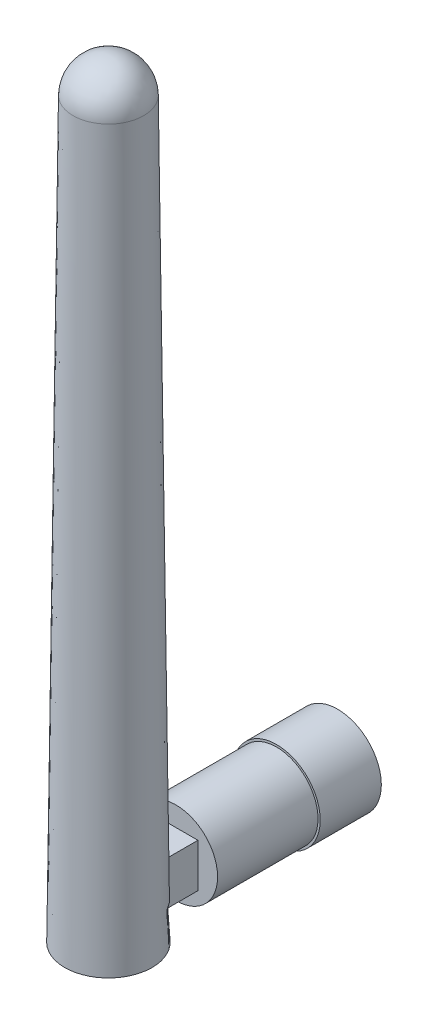
SolidWorks part; units mm, degrees
ref_plane "Front Plane" through (0, 0, 0) normal (0, 0, 1) x (1, 0, 0)
ref_plane "Top Plane" through (0, 0, 0) normal (0, 1, 0) x (1, 0, 0)
ref_plane "Right Plane" through (0, 0, 0) normal (1, 0, 0) x (0, 0, -1)
sketch "Sketch1" plane through (0, 0, 0) normal (0, 0, 1) x (1, 0, 0)
  circle A0 centre (0, 0) radius 5
  dimension "D1" = 10
extrude "Boss-Extrude1" add sketch "Sketch1" along normal blind 7
sketch "Sketch2" plane through (0, 0, 7) normal (0, 0, 1) x (1, 0, 0)
  circle A0 centre (0, 0) radius 4.75
  dimension "D1" = 9.5
extrude "Boss-Extrude2" add sketch "Sketch2" along normal blind 11.5
sketch "Sketch3" plane through (0, 0, 0) normal (0, 1, 0) x (1, 0, 0)
  line L0 (5, 0) -> (-5, 0) construction
  circle A0 centre (0, -26.25) radius 4.75
  dimension "D1" = 9.5
  dimension "D2" = 31
ref_plane "Plane1" through (0, 0, 26.25) normal (0, 0, 1) x (1, 0, 0)
sketch "Sketch4" plane through (0, 0, 26.25) normal (0, 0, 1) x (1, 0, 0)
  line L0 (0, -5) -> (-5, -5)
  line L1 (-5, -5) -> (-4.0455, 79.0003)
  line L2 (0, -1000) -> (0, 49000) construction
  line L3 (4.75, 0) -> (-4.75, 0) construction
  line L6 (0, 83) -> (0, -5)
  circle A0 centre (0, 0) radius 5 construction
  arc A2 (0, 83) -> (-4.0455, 79.0003) centre (0, 78.9543) ccw
  point P10 (0, 0)
  point P12 (0, 83)
  point P13 (0, -5)
  dimension "D1" = 4.0457
  dimension "D4" = 88
revolve "Revolve2" add sketch "Sketch4" angle 360 about L2
sketch "Sketch5" plane through (0, 0, 18.5) normal (0, 0, 1) x (1, 0, 0)
  line L1 (-2.5, -2.5) -> (2.5, -2.5)
  line L2 (-2.5, -2.5) -> (-2.5, 2.5)
  line L3 (-2.5, 2.5) -> (2.5, 2.5)
  line L4 (2.5, -2.5) -> (2.5, 2.5)
  dimension "D1" = 2.5
  dimension "D2" = 2.5
  dimension "D3" = 5
  dimension "D4" = 5
extrude "Boss-Extrude3" add sketch "Sketch5" along normal blind 10.5
sketch "Sketch6" plane through (0, -5, 0) normal (0, -1, 0) x (1, 0, 0)
  line L0 (2.5, 21.9527) -> (2.5, 18.5) construction
  line L1 (-2.5, 18.5) -> (2.5, 18.5)
  line L2 (-2.5, 18.5) -> (-2.5, 29)
  line L3 (-2.5, 29) -> (2.5, 29)
  line L4 (2.5, 18.5) -> (2.5, 29)
  dimension "D1" = 10.5
extrude "Cut-Extrude1" cut sketch "Sketch6" against normal up to surface (2.5 mm away) up to face at (0, -2.5, 20.0578)
